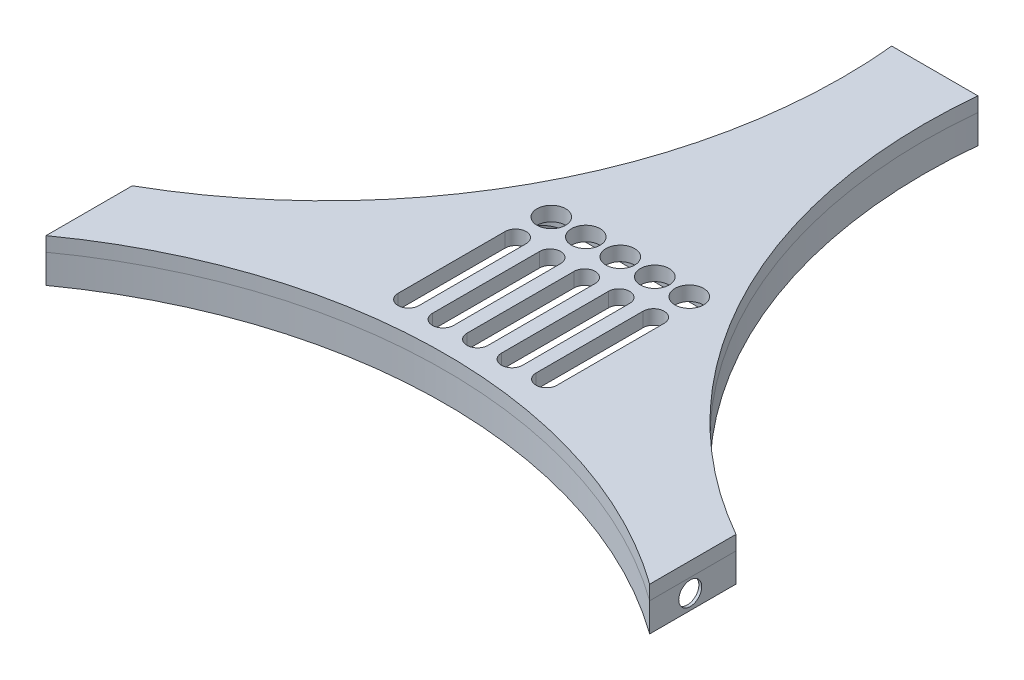
SolidWorks part; units mm, degrees
ref_plane "Front Plane" through (0, 0, 0) normal (0, 0, 1) x (1, 0, 0)
ref_plane "Top Plane" through (0, 0, 0) normal (0, 1, 0) x (1, 0, 0)
ref_plane "Right Plane" through (0, 0, 0) normal (1, 0, 0) x (0, 0, -1)
sketch "Sketch1" plane through (0, 0, 0) normal (0, 1, 0) x (1, 0, 0)
  line L0 (0, 0) -> (0, 0.58) construction
  line L1 (10.5, 0.58) -> (10.5, -2.42)
  line L2 (-1.5, 18) -> (1.5, 18)
  line L3 (-10.5, 0.58) -> (-10.5, -2.42)
  line L4 (-10.5, -2.42) -> (10.5, -2.42)
  line L5 (-11.1498, 9) -> (11.1498, 9) construction
  line L6 (0, 0) -> (0, 0.58) construction
  line L7 (0, 0) -> (0, 0.58)
  line L9 (-10.5, 0.58) -> (-10.5286, 0.5197)
  line L10 (0, 0.9598) -> (0, 18) construction
  arc A0 (1.5, 18) -> (10.5, 0.58) centre (19.4117, 16.2191) ccw
  arc A1 (-1.5, 18) -> (-10.5, 0.58) centre (-19.4117, 16.2191) cw
  arc A2 (-10.5, -2.42) -> (10.5, -2.42) centre (0, -17.0402) cw
  point P6 (0, 9)
  point P16 (0, 9)
  dimension "D2" = 3
  dimension "D4" = 18
  dimension "D5" = 21
  dimension "D6" = 18
  dimension "D9" = 11.42
  dimension "D1" = 18
  dimension "D3" = 3
  dimension "D7" = 9
  dimension "D10" = 0.9598
extrude "Boss-Extrude1" add sketch "Sketch1" along normal blind 0.5
sketch "Sketch2" plane through (0, 0, 0) normal (0, -1, 0) x (1, 0, 0)
  line L1 (-2.5193, -1.0672) -> (2.5193, -1.0672)
  line L2 (-3.5193, -2.0672) -> (-3.5193, -6.7674)
  line L3 (-2.5193, -7.7674) -> (2.5193, -7.7674)
  line L4 (3.5193, -2.0672) -> (3.5193, -6.7674)
  line L5 (-3.5193, -1.0672) -> (3.5193, -7.7674) construction
  line L6 (-3.5193, -7.7674) -> (3.5193, -1.0672) construction
  arc A0 (10.5, -0.58) -> (1.5, -18) centre (19.4117, -16.2191) ccw construction
  arc A1 (2.5193, -7.7674) -> (3.5193, -6.7674) centre (2.5193, -6.7674) ccw
  arc A2 (-2.5193, -7.7674) -> (-3.5193, -6.7674) centre (-2.5193, -6.7674) cw
  arc A3 (-2.5193, -1.0672) -> (-3.5193, -2.0672) centre (-2.5193, -2.0672) ccw
  arc A4 (2.5193, -1.0672) -> (3.5193, -2.0672) centre (2.5193, -2.0672) cw
  point P0 (0, -4.4173)
  dimension "D3" = 1
  dimension "D1" = 6.7001
  dimension "D2" = 7.0386
extrude "Extrude-Thin2" add sketch "Sketch2" along normal blind 0.5 thin thin type one direction wall 0.1
sketch "Sketch4" plane through (0, 0, 0) normal (0, -1, 0) x (1, 0, 0)
  line L0 (-2.272, -1.9619) -> (-2.272, -5.6874) construction
  line L1 (-1.9051, -1.9619) -> (-1.9051, -5.6874)
  line L2 (-2.6389, -1.9619) -> (-2.6389, -5.6874)
  line L3 (-1.072, -1.9619) -> (-1.072, -5.6874) construction
  line L4 (-0.7051, -1.9619) -> (-0.7051, -5.6874)
  line L5 (-1.4389, -1.9619) -> (-1.4389, -5.6874)
  line L6 (0.128, -1.9619) -> (0.128, -5.6874) construction
  line L7 (0.4949, -1.9619) -> (0.4949, -5.6874)
  line L8 (-0.2389, -1.9619) -> (-0.2389, -5.6874)
  line L9 (1.328, -1.9619) -> (1.328, -5.6874) construction
  line L10 (1.6949, -1.9619) -> (1.6949, -5.6874)
  line L11 (0.9611, -1.9619) -> (0.9611, -5.6874)
  line L12 (2.528, -1.9619) -> (2.528, -5.6874) construction
  line L13 (2.8949, -1.9619) -> (2.8949, -5.6874)
  line L14 (2.1611, -1.9619) -> (2.1611, -5.6874)
  arc A0 (-1.9051, -1.9619) -> (-2.6389, -1.9619) centre (-2.272, -1.9619) ccw
  arc A1 (-2.6389, -5.6874) -> (-1.9051, -5.6874) centre (-2.272, -5.6874) ccw
  circle A2 centre (-2.272, -6.9292) radius 0.4993
  circle A3 centre (-1.072, -6.9292) radius 0.4993
  arc A4 (-0.7051, -1.9619) -> (-1.4389, -1.9619) centre (-1.072, -1.9619) ccw
  arc A5 (-1.4389, -5.6874) -> (-0.7051, -5.6874) centre (-1.072, -5.6874) ccw
  circle A6 centre (0.128, -6.9292) radius 0.4993
  arc A7 (0.4949, -1.9619) -> (-0.2389, -1.9619) centre (0.128, -1.9619) ccw
  arc A8 (-0.2389, -5.6874) -> (0.4949, -5.6874) centre (0.128, -5.6874) ccw
  circle A9 centre (1.328, -6.9292) radius 0.4993
  arc A10 (1.6949, -1.9619) -> (0.9611, -1.9619) centre (1.328, -1.9619) ccw
  arc A11 (0.9611, -5.6874) -> (1.6949, -5.6874) centre (1.328, -5.6874) ccw
  circle A12 centre (2.528, -6.9292) radius 0.4993
  arc A13 (2.8949, -1.9619) -> (2.1611, -1.9619) centre (2.528, -1.9619) ccw
  arc A14 (2.1611, -5.6874) -> (2.8949, -5.6874) centre (2.528, -5.6874) ccw
  point P2 (-2.272, -3.8246)
  point P13 (-1.072, -3.8246)
  point P22 (0.128, -3.8246)
  point P31 (1.328, -3.8246)
  point P40 (2.528, -3.8246)
  dimension "D1" = 5
extrude "Cut-Extrude1" cut sketch "Sketch4" against normal blind 0.5
ref_plane "Plane1" through (0, -11, 0) normal (0, 1, 0) x (1, 0, 0)
sketch "Sketch5" plane through (0, -11, 0) normal (0, 1, 0) x (1, 0, 0)
  line L0 (-10.5, 0.58) -> (-10.5, -2.42) construction
  line L1 (10.5, 0.58) -> (10.5, -2.42) construction
  line L2 (-1.5, 18) -> (1.5, 18) construction
  line L3 (-10.5, 0.58) -> (-10.5, -2.42)
  line L4 (10.5, 0.58) -> (10.5, -2.42)
  line L5 (-1.5, 18) -> (1.5, 18)
  line L6 (-10.5, -2.42) -> (10.5, -2.42) construction
  line L7 (0, 18) -> (0, -2.42) construction
  arc A0 (10.5, -2.42) -> (-10.5, -2.42) centre (0, -17.0402) ccw construction
  arc A1 (1.5, 18) -> (10.5, 0.58) centre (19.4117, 16.2191) ccw construction
  arc A2 (-10.5, 0.58) -> (-1.5, 18) centre (-19.4117, 16.2191) ccw construction
  arc A3 (10.5, -2.42) -> (-10.5, -2.42) centre (0, -17.0402) ccw
  arc A4 (1.5, 18) -> (10.5, 0.58) centre (19.4117, 16.2191) ccw
  arc A5 (-10.5, 0.58) -> (-1.5, 18) centre (-19.4117, 16.2191) ccw
  dimension "D1" = 18
  dimension "D2" = 18
  dimension "D3" = 18
  dimension "D4" = 3
  dimension "D5" = 3
  dimension "D6" = 21
  dimension "D7" = 20.42
sketch "Sketch6" plane through (0, 0, 0) normal (0, -1, 0) x (1, 0, 0)
  line L0 (-10.5, -0.58) -> (-10.5, 2.42) construction
  line L1 (10.5, -0.58) -> (10.5, 2.42) construction
  line L2 (-1.5, -18) -> (1.5, -18) construction
  line L3 (-10.5, -0.58) -> (-10.5, 2.42)
  line L4 (10.5, -0.58) -> (10.5, 2.42)
  line L5 (-1.5, -18) -> (1.5, -18)
  arc A0 (-10.5, 2.42) -> (10.5, 2.42) centre (0, 17.0402) ccw construction
  arc A1 (10.5, -0.58) -> (1.5, -18) centre (19.4117, -16.2191) ccw construction
  arc A2 (-1.5, -18) -> (-10.5, -0.58) centre (-19.4117, -16.2191) ccw construction
  arc A3 (-10.5, 2.42) -> (10.5, 2.42) centre (0, 17.0402) ccw
  arc A4 (10.5, -0.58) -> (1.5, -18) centre (19.4117, -16.2191) ccw
  arc A5 (-1.5, -18) -> (-10.5, -0.58) centre (-19.4117, -16.2191) ccw
extrude "Extrude-Thin3" add sketch "Sketch6" along normal blind 1 separate body thin
sketch "Sketch12" plane through (-10.5, 0, 0) normal (-1, 0, 0) x (0, 0, 1)
  circle A0 centre (0.9256, -0.5349) radius 0.4
  point P2 (0.9256, -0.5349)
  dimension "D1" = 0.8
extrude "Cut-Extrude2" cut sketch "Sketch12" against normal mid plane 1
sketch "Sketch13" plane through (10.5, 0, 0) normal (1, 0, 0) x (0, 0, -1)
  circle A0 centre (-1.0099, -0.479) radius 0.4
  dimension "D1" = 0.8
extrude "Cut-Extrude3" cut sketch "Sketch13" against normal mid plane 1
sketch "Sketch14" plane through (0, 0, -18) normal (0, 0, -1) x (-1, 0, 0)
  circle A0 centre (0, -0.4257) radius 0.4
  dimension "D1" = 0.8
extrude "Cut-Extrude4" cut sketch "Sketch14" against normal blind 1
